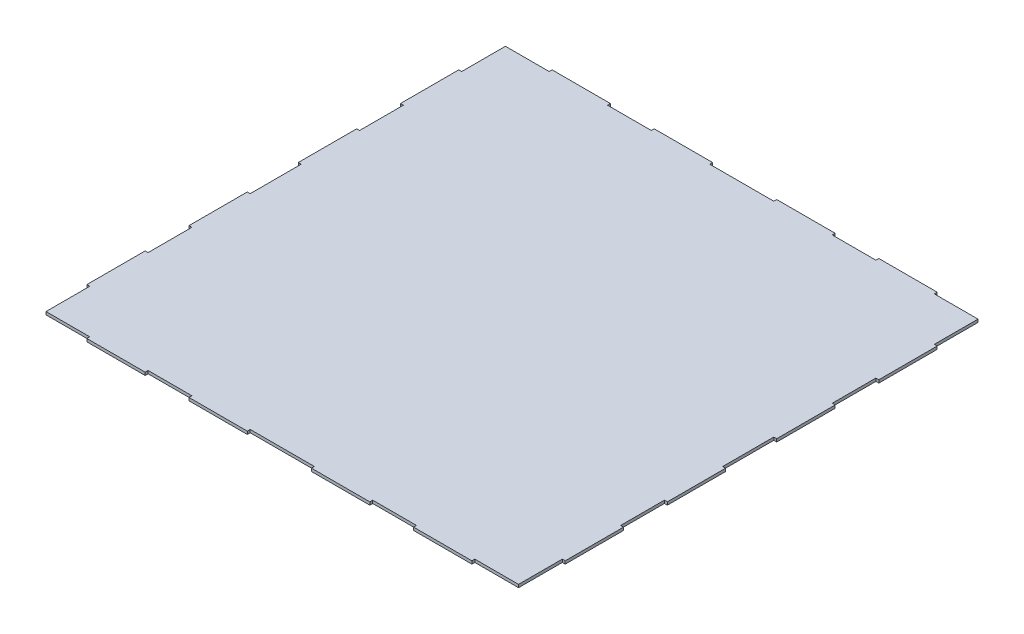
SolidWorks part; units mm, degrees
material "ABS PC"
ref_plane "Front Plane" through (0, 0, 0) normal (0, 0, 1) x (1, 0, 0)
ref_plane "Top Plane" through (0, 0, 0) normal (0, 1, 0) x (1, 0, 0)
ref_plane "Right Plane" through (0, 0, 0) normal (1, 0, 0) x (0, 0, -1)
sketch "Sketch1" plane through (0, 0, 0) normal (0, 1, 0) x (1, 0, 0)
  line L0 (64, -157.5) -> (162, -157.5)
  line L1 (-162, 157.5) -> (162, 157.5)
  line L2 (-162, 157.5) -> (-162, -157.5)
  line L3 (-162, -157.5) -> (-66, -157.5)
  line L4 (162, 157.5) -> (162, -157.5)
  line L5 (-162, 157.5) -> (162, -157.5) construction
  line L6 (-162, -157.5) -> (162, 157.5) construction
  line L8 (-66, -157.5) -> (-66, -193.5)
  line L9 (-66, -193.5) -> (64, -193.5)
  line L10 (64, -157.5) -> (64, -193.5)
  line L11 (-66, -157.5) -> (64, -157.5) construction
  circle A0 centre (-51, -175.5) radius 4.25
  circle A1 centre (49, -175.5) radius 4.25
  point P0 (0, 0)
  dimension "D6" = 8.5
  dimension "D7" = 8.5
  dimension "D1" = 324
  dimension "D2" = 315
  dimension "D3" = 130
  dimension "D4" = 96
  dimension "D5" = 36
  dimension "D8" = 15
  dimension "D9" = 15
  dimension "D10" = 18
extrude "Boss-Extrude1" add sketch "Sketch1" along normal blind 2
sketch "Sketch2" plane through (0, 2, 0) normal (0, 1, 0) x (1, 0, 0)
  line L1 (-66, -157.5) -> (64, -157.5)
  line L2 (-66, -157.5) -> (-66, -193.5)
  line L3 (-66, -193.5) -> (64, -193.5)
  line L4 (64, -157.5) -> (64, -193.5)
extrude "Cut-Extrude1" cut sketch "Sketch2" against normal through all both and the other way through all
sketch "Sketch5" plane through (0, 0, 0) normal (0, -1, 0) x (1, 0, 0)
  line L0 (-162, -157.5) -> (-162, 157.5) construction
  line L1 (-162, 127.5) -> (-164, 127.5)
  line L2 (-162, 127.5) -> (-162, 87.5)
  line L3 (-162, 87.5) -> (-164, 87.5)
  line L4 (-164, 127.5) -> (-164, 87.5)
  line L5 (-162, 157.5) -> (162, 157.5) construction
  line L6 (-162, 57.5) -> (-164, 57.5)
  line L7 (-162, 57.5) -> (-162, 17.5)
  line L8 (-162, 17.5) -> (-164, 17.5)
  line L9 (-164, 57.5) -> (-164, 17.5)
  line L10 (-132, 157.5) -> (-92, 157.5)
  line L11 (-132, 157.5) -> (-132, 159.5)
  line L12 (-132, 159.5) -> (-92, 159.5)
  line L13 (-92, 157.5) -> (-92, 159.5)
  line L14 (162, -157.5) -> (-162, -157.5) construction
  line L15 (-62, 157.5) -> (-22, 157.5)
  line L16 (-62, 157.5) -> (-62, 159.5)
  line L17 (-62, 159.5) -> (-22, 159.5)
  line L18 (-22, 157.5) -> (-22, 159.5)
  line L19 (-162, -127.5) -> (-164, -127.5)
  line L20 (-162, -127.5) -> (-162, -87.5)
  line L21 (-162, -87.5) -> (-164, -87.5)
  line L22 (-164, -127.5) -> (-164, -87.5)
  line L23 (-162, -57.5) -> (-164, -57.5)
  line L24 (-162, -57.5) -> (-162, -17.5)
  line L25 (-162, -17.5) -> (-164, -17.5)
  line L26 (-164, -57.5) -> (-164, -17.5)
  line L27 (0, -55) -> (0, 55) construction
  line L28 (-132, -157.5) -> (-92, -157.5)
  line L29 (-132, -157.5) -> (-132, -159.5)
  line L30 (-132, -159.5) -> (-92, -159.5)
  line L31 (-92, -157.5) -> (-92, -159.5)
  line L32 (-62, -157.5) -> (-22, -157.5)
  line L33 (-62, -157.5) -> (-62, -159.5)
  line L34 (-62, -159.5) -> (-22, -159.5)
  line L35 (-22, -157.5) -> (-22, -159.5)
  line L36 (22, -157.5) -> (22, -159.5)
  line L37 (62, -159.5) -> (22, -159.5)
  line L38 (62, -157.5) -> (62, -159.5)
  line L39 (62, -157.5) -> (22, -157.5)
  line L40 (92, -157.5) -> (92, -159.5)
  line L41 (132, -159.5) -> (92, -159.5)
  line L42 (132, -157.5) -> (132, -159.5)
  line L43 (132, -157.5) -> (92, -157.5)
  line L44 (164, -57.5) -> (164, -17.5)
  line L45 (162, -17.5) -> (164, -17.5)
  line L46 (162, -57.5) -> (162, -17.5)
  line L47 (162, -57.5) -> (164, -57.5)
  line L48 (164, -127.5) -> (164, -87.5)
  line L49 (162, -87.5) -> (164, -87.5)
  line L50 (162, -127.5) -> (162, -87.5)
  line L51 (162, -127.5) -> (164, -127.5)
  line L52 (22, 157.5) -> (22, 159.5)
  line L53 (62, 159.5) -> (22, 159.5)
  line L54 (62, 157.5) -> (62, 159.5)
  line L55 (62, 157.5) -> (22, 157.5)
  line L56 (92, 157.5) -> (92, 159.5)
  line L57 (132, 159.5) -> (92, 159.5)
  line L58 (132, 157.5) -> (132, 159.5)
  line L59 (132, 157.5) -> (92, 157.5)
  line L60 (164, 57.5) -> (164, 17.5)
  line L61 (162, 17.5) -> (164, 17.5)
  line L62 (162, 57.5) -> (162, 17.5)
  line L63 (162, 57.5) -> (164, 57.5)
  line L64 (164, 127.5) -> (164, 87.5)
  line L65 (162, 87.5) -> (164, 87.5)
  line L66 (162, 127.5) -> (162, 87.5)
  line L67 (162, 127.5) -> (164, 127.5)
  dimension "D1" = 30
  dimension "D2" = 40
  dimension "D3" = 2
  dimension "D4" = 2
  dimension "D5" = 30
  dimension "D6" = 40
  dimension "D7" = 30
  dimension "D8" = 40
  dimension "D9" = 2
  dimension "D10" = 30
  dimension "D11" = 40
  dimension "D12" = 2
  dimension "D13" = 30
  dimension "D14" = 40
  dimension "D15" = 2
  dimension "D16" = 30
  dimension "D17" = 40
  dimension "D18" = 2
  dimension "D19" = 30
  dimension "D20" = 40
  dimension "D21" = 2
  dimension "D22" = 30
  dimension "D23" = 40
  dimension "D24" = 2
extrude "Boss-Extrude2" add sketch "Sketch5" against normal blind 2
